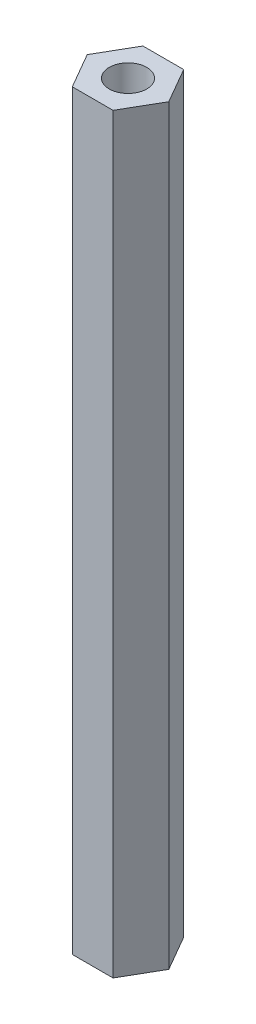
SolidWorks part; units mm, degrees
material "黄铜"
ref_plane "前视基准面" through (0, 0, 0) normal (0, 0, 1) x (1, 0, 0)
ref_plane "上视基准面" through (0, 0, 0) normal (0, 1, 0) x (1, 0, 0)
ref_plane "右视基准面" through (0, 0, 0) normal (1, 0, 0) x (0, 0, -1)
sketch "草图1" plane through (0, 0, 0) normal (0, 1, 0) x (1, 0, 0)
  line L1 (2.7135, 0) -> (1.3568, 2.35)
  line L2 (1.3568, 2.35) -> (-1.3568, 2.35)
  line L3 (-1.3568, 2.35) -> (-2.7135, 0)
  line L4 (-2.7135, 0) -> (-1.3568, -2.35)
  line L5 (-1.3568, -2.35) -> (1.3568, -2.35)
  line L6 (1.3568, -2.35) -> (2.7135, 0)
  circle A1 centre (0, 0) radius 2.35 construction
  dimension "D1" = 4.7
extrude "凸台-拉伸1" add sketch "草图1" along normal blind 50
hole_wizard "M3 螺纹孔1" positions "草图2" profile "草图4" tap size "M3" standard "GB" end condition through all
sketch "草图2" plane through (0, 50, 0) normal (0, 1, 0) x (1, 0, 0)
  point P0 (0, 0)
sketch "草图4" plane through (0, 50, 0) normal (1, 0, 0) x (0, 0, 1)
  line L0 (0, 0) -> (0, 50)
  line L1 (0, 50) -> (1.25, 50)
  line L2 (1.25, 50) -> (1.25, 0)
  line L5 (1.25, 0) -> (0, 0)
  line L11 (0, -6.35) -> (0, 107.95) construction
  dimension "通孔螺纹孔钻头直径" = 2.5
  dimension "通孔螺纹孔钻头深度" = 50
cosmetic thread "孔螺蚊线1" parameters "D2"=3
